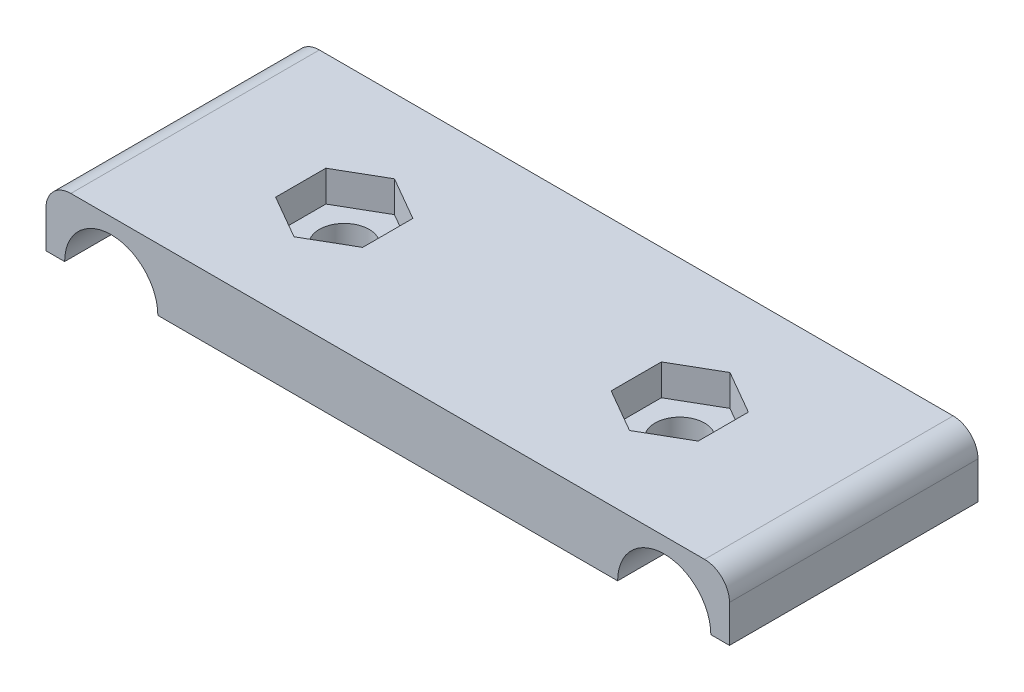
SolidWorks part; units mm, degrees
ref_plane "前基準面" through (0, 0, 0) normal (0, 0, 1) x (1, 0, 0)
ref_plane "上基準面" through (0, 0, 0) normal (0, 1, 0) x (1, 0, 0)
ref_plane "右基準面" through (0, 0, 0) normal (1, 0, 0) x (0, 0, -1)
sketch "草圖1" plane through (0, 0, 0) normal (0, 0, 1) x (1, 0, 0)
  line L0 (-18.5, -2.5) -> (18.5, -2.5)
  line L1 (-27.5, 2.5) -> (27.5, 2.5)
  line L2 (-27.5, 2.5) -> (-27.5, -2.5)
  line L3 (-27.5, -2.5) -> (-26, -2.5)
  line L4 (27.5, 2.5) -> (27.5, -2.5)
  line L5 (26, -2.5) -> (27.5, -2.5)
  arc A0 (-18.5, -2.5) -> (-26, -2.5) centre (-22.25, -2.5) ccw
  arc A1 (26, -2.5) -> (18.5, -2.5) centre (22.25, -2.5) ccw
  point P4 (0, 2.5)
  point P6 (-27.5, 0)
  point P9 (-18.5, -2.5)
  dimension "D3" = 7.5
  dimension "D6" = 7.5
  dimension "D1" = 55
  dimension "D2" = 5
  dimension "D4" = 22.25
  dimension "D5" = 18.5
  dimension "D7" = 22.25
extrude "填料-伸長1" add sketch "草圖1" along normal blind 20
fillet "圓角1" radius 2 2 edges at (27.5, 2.5, 10) (-27.5, 2.5, 10)
sketch "草圖2" plane through (0, 2.5, 0) normal (0, 1, 0) x (1, 0, 0)
  line L0 (27.5, 0) -> (27.5, -20) construction
  line L1 (-27.5, -20) -> (-27.5, 0) construction
  circle A0 centre (13.5, -10) radius 2
  circle A1 centre (-13.5, -10) radius 2
  dimension "D1" = 4
  dimension "D2" = 4
  dimension "D3" = 14
  dimension "D4" = 14
extrude "除料-伸長1" cut sketch "草圖2" against normal through all
sketch "草圖3" plane through (0, 2.5, 0) normal (0, 1, 0) x (1, 0, 0)
  line L1 (13.5, -5.9585) -> (10, -7.9793)
  line L2 (10, -7.9793) -> (10, -12.0207)
  line L3 (10, -12.0207) -> (13.5, -14.0415)
  line L4 (13.5, -14.0415) -> (17, -12.0207)
  line L5 (17, -12.0207) -> (17, -7.9793)
  line L6 (17, -7.9793) -> (13.5, -5.9585)
  line L7 (-13.5, -5.9585) -> (-17, -7.9793)
  line L8 (-17, -7.9793) -> (-17, -12.0207)
  line L9 (-17, -12.0207) -> (-13.5, -14.0415)
  line L10 (-13.5, -14.0415) -> (-10, -12.0207)
  line L11 (-10, -12.0207) -> (-10, -7.9793)
  line L12 (-10, -7.9793) -> (-13.5, -5.9585)
  circle A0 centre (13.5, -10) radius 3.5 construction
  circle A1 centre (-13.5, -10) radius 3.5 construction
  point P10 (13.5, -6.0851)
  dimension "D1" = 7
  dimension "D2" = 7
extrude "除料-伸長2" cut sketch "草圖3" against normal blind 2.5
